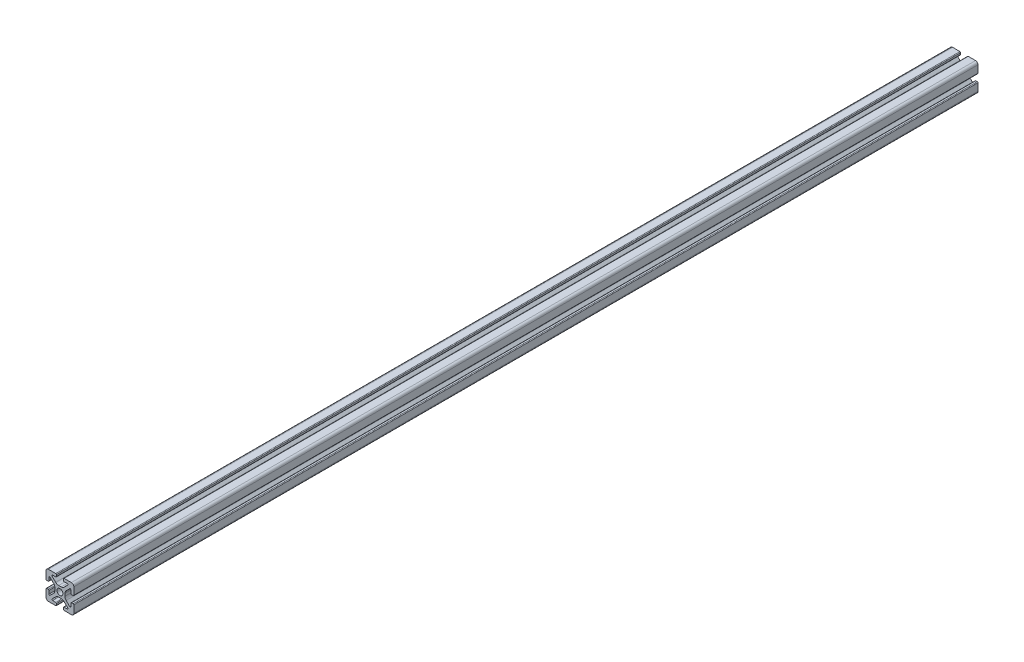
SolidWorks part; units mm, degrees
material "6063-T6"
ref_plane "Front Plane" through (0, 0, 0) normal (0, 0, 1) x (1, 0, 0)
ref_plane "Top Plane" through (0, 0, 0) normal (0, 1, 0) x (1, 0, 0)
ref_plane "Right Plane" through (0, 0, 0) normal (1, 0, 0) x (0, 0, -1)
sketch "Sketch2" plane through (0, 0, 0) normal (0, 0, 1) x (1, 0, 0)
  line L0 (0, 10) -> (0, -10) construction
  line L1 (-10, 0) -> (10, 0) construction
  line L2 (2.5, -10) -> (10, -10)
  line L3 (10, -10) -> (10, -2.5)
  line L4 (2.5, -10) -> (2.5, -7.9246)
  line L5 (2.5, -7.9246) -> (6.4571, -7.9246)
  line L6 (6.4571, -7.9246) -> (2.1325, -3.6)
  line L7 (0, 0) -> (10, -10) construction
  line L8 (10, -2.5) -> (7.9246, -2.5)
  line L9 (7.9246, -2.5) -> (7.9246, -6.4571)
  line L10 (7.9246, -6.4571) -> (3.6, -2.1325)
  line L11 (5.7623, -4.2948) -> (4.2948, -5.7623) construction
  circle A0 centre (0, 0) radius 2.15
  arc A1 (5.25, -7.9246) -> (5.6036, -7.0711) centre (5.25, -7.4246) ccw construction
  point P8 (0, -3.6)
  point P16 (5.0286, -5.0286)
  dimension "Center Hole Diameter" = 4.3
  dimension "D3" = 0.5
  dimension "Rail Height" = 20
  dimension "Rail Width" = 20
  dimension "T-Slot Width" = 5
  dimension "Slot Depth" = 6.4
  dimension "Slot Inner Width" = 11.5
sketch "Sketch3" plane through (0, 0, 0) normal (1, 0, 0) x (0, 0, -1)
  line L0 (-325, -10) -> (325, -10) construction
  line L1 (-299.6, 0) -> (299.6, 0) construction
  line L2 (0, 10) -> (0, -10) construction
  line L3 (0, 10) -> (0, -10) construction
  point P6 (-299.6, 0)
  point P8 (299.6, 0)
  dimension "Length" = 650
  dimension "D1" = 25.4
sketch "Sketch4" plane through (0, 0, 0) normal (0, 0, 1) x (1, 0, 0)
  line L0 (3, -10) -> (8.25, -10)
  line L1 (2.5, -10) -> (10, -10) construction
  line L2 (2.5, -10) -> (2.5, -7.9246) construction
  line L3 (2.5, -7.9246) -> (6.4571, -7.9246) construction
  line L4 (2.5, -8.4246) -> (2.5, -9.5)
  line L5 (3, -7.9246) -> (5.25, -7.9246)
  line L6 (0, -3.6) -> (0.8898, -3.6)
  line L7 (6.4571, -7.9246) -> (2.1325, -3.6) construction
  line L8 (3.0112, -4.4787) -> (5.6036, -7.0711)
  line L9 (10, -10) -> (10, -2.5) construction
  line L10 (7.9246, -6.4571) -> (3.6, -2.1325) construction
  line L11 (7.9246, -2.5) -> (7.9246, -6.4571) construction
  line L12 (7.9246, -5.25) -> (7.9246, -3)
  line L13 (10, -2.5) -> (7.9246, -2.5) construction
  line L14 (8.4246, -2.5) -> (9.5, -2.5)
  line L15 (10, -3) -> (10, -8.25)
  line L16 (7.0711, -5.6036) -> (4.4787, -3.0112)
  line L17 (3.6, 0) -> (3.6, -0.8898)
  line L18 (-10, 0) -> (10, 0) construction
  line L19 (0, -3.6) -> (0, -2.15)
  line L20 (0, 10) -> (0, -10) construction
  line L21 (3.6, 0) -> (2.15, 0)
  arc A0 (2.5, -9.5) -> (3, -10) centre (3, -9.5) ccw
  arc A1 (5.25, -7.9246) -> (5.6036, -7.0711) centre (5.25, -7.4246) ccw construction
  arc A2 (2.5, -8.4246) -> (3, -7.9246) centre (3, -8.4246) cw
  arc A3 (5.25, -7.9246) -> (5.6036, -7.0711) centre (5.25, -7.4246) ccw
  arc A4 (0.8898, -3.6) -> (3.0112, -4.4787) centre (0.8898, -6.6) cw
  arc A5 (8.25, -10) -> (10, -8.25) centre (8.25, -8.25) ccw
  arc A6 (7.0711, -5.6036) -> (7.9246, -5.25) centre (7.4246, -5.25) ccw
  arc A7 (7.9246, -3) -> (8.4246, -2.5) centre (8.4246, -3) cw
  arc A8 (9.5, -2.5) -> (10, -3) centre (9.5, -3) cw
  arc A9 (4.4787, -3.0112) -> (3.6, -0.8898) centre (6.6, -0.8898) cw
  circle A10 centre (0, 0) radius 2.15 construction
  arc A11 (0, -2.15) -> (2.15, 0) centre (0, 0) ccw
  dimension "D1" = 1.75
  dimension "D2" = 3
extrude "Boss-Extrude1" add sketch "Sketch4" along normal mid plane 650
mirror "Mirror1" about plane through (0, 0, 0) normal (1, 0, 0) of bodies 134
mirror "Mirror2" about plane through (0, 0, 0) normal (0, 1, 0) of bodies 135
equation "\"D3@Sketch2\"=\"T-Slot Width@Sketch2\"*0.1"
equation "\"D1@Sketch4\"=\"D3@Sketch2\"*3.5"
equation "\"D2@Sketch4\"=\"D3@Sketch2\"*6"
equation "\"D1@Boss-Extrude1\"=\"Length@Sketch3\""
